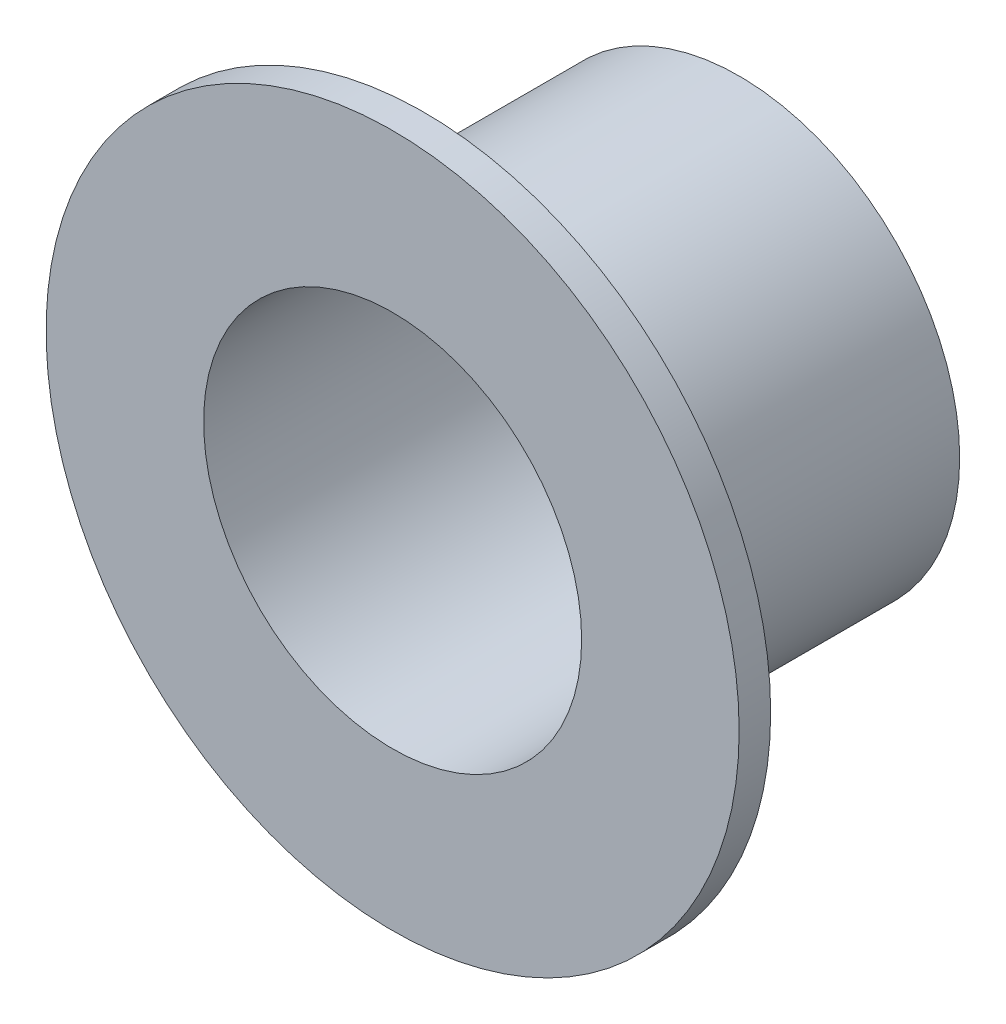
SolidWorks part; units mm, degrees
material "ABS"
ref_plane "Płaszczyzna przednia" through (0, 0, 0) normal (0, 0, 1) x (1, 0, 0)
ref_plane "Płaszczyzna górna" through (0, 0, 0) normal (0, 1, 0) x (1, 0, 0)
ref_plane "Płaszczyzna prawa" through (0, 0, 0) normal (1, 0, 0) x (0, 0, -1)
sketch "Szkic1" plane through (0, 0, 0) normal (0, 0, 1) x (1, 0, 0)
  circle A0 centre (0, 0) radius 3
  circle A1 centre (0, 0) radius 3.5
  dimension "D1" = 6
  dimension "D2" = 7
extrude "Dodanie-wyciągnięcie1" add sketch "Szkic1" along normal blind 5.5
sketch "Szkic2" plane through (0, 0, 5.5) normal (0, 0, 1) x (1, 0, 0)
  circle A0 centre (0, 0) radius 3
  circle A1 centre (0, 0) radius 5.5
  dimension "D1" = 11
  dimension "D2" = 6
extrude "Dodanie-wyciągnięcie2" add sketch "Szkic2" against normal blind 0.5
